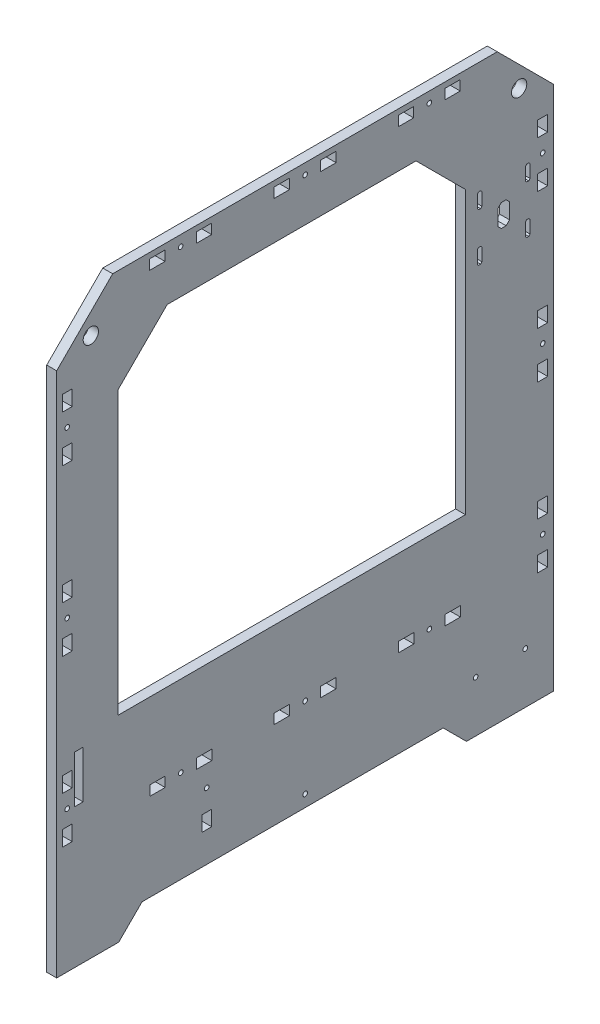
SolidWorks part; units mm, degrees
ref_plane "Front Plane" through (0, 0, 0) normal (0, 0, 1) x (1, 0, 0)
ref_plane "Top Plane" through (0, 0, 0) normal (0, 1, 0) x (1, 0, 0)
ref_plane "Right Plane" through (0, 0, 0) normal (1, 0, 0) x (0, 0, -1)
sketch "Sketch1" plane through (0, 0, 0) normal (1, 0, 0) x (0, 0, -1)
  line L0 (-34.3717, -25.3248) -> (-34.3717, -206.8248)
  line L1 (-37.635, 41.2752) -> (210.165, 41.2752)
  line L3 (-56.735, -213.3748) -> (-56.735, -243.8748)
  line L4 (228.265, -268.8248) -> (196.265, -300.8248) construction
  line L7 (230.4513, -30.9236) -> (229.2087, -30.9236)
  line L9 (176.665, 34.4752) -> (156.065, 34.4752) construction
  line L10 (230.4513, -40.9255) -> (229.2087, -40.9255)
  line L11 (215.8783, -58.6805) -> (212.7717, -58.6805)
  line L14 (200.33, -31.8023) -> (199.4513, -30.9236)
  line L15 (199.4513, -30.9236) -> (198.2087, -30.9236)
  line L16 (198.2087, -30.9236) -> (197.33, -31.8023)
  line L17 (197.33, -31.8023) -> (197.33, -40.0468)
  line L18 (199.4513, -40.9255) -> (198.2087, -40.9255)
  line L19 (228.33, -40.0468) -> (228.33, -31.8023)
  line L21 (200.33, -40.0468) -> (200.33, -31.8023)
  line L22 (231.33, -31.8023) -> (230.4513, -30.9236)
  line L25 (198.2087, -40.9255) -> (197.33, -40.0468)
  line L26 (200.33, -40.0468) -> (199.4513, -40.9255)
  line L28 (231.33, -31.8023) -> (231.33, -40.0468)
  line L30 (231.33, -40.0468) -> (230.4513, -40.9255)
  line L31 (229.2087, -30.9236) -> (228.33, -31.8023)
  line L32 (96.665, 34.4752) -> (76.065, 34.4752) construction
  line L34 (16.465, 34.4752) -> (-4.135, 34.4752) construction
  line L35 (-73.735, 5.1752) -> (-73.735, -333.6748)
  line L36 (-34.3717, -206.8248) -> (189.675, -206.8248)
  line L37 (-66.935, -19.5248) -> (-66.935, -40.1248) construction
  line L38 (-73.735, 5.1752) -> (-37.635, 41.2752)
  line L39 (-66.935, -125.9248) -> (-66.935, -146.5248) construction
  line L40 (189.675, -206.8248) -> (189.675, -25.3248)
  line L41 (-66.935, -232.3248) -> (-66.935, -252.9248) construction
  line L42 (246.265, 5.1752) -> (246.265, -333.6748)
  line L43 (-4.035, -259.1248) -> (16.565, -259.1248) construction
  line L44 (176.765, -259.1248) -> (156.165, -259.1248) construction
  line L45 (229.2087, -40.9255) -> (228.33, -40.0468)
  line L46 (230.4513, -61.9236) -> (229.2087, -61.9236)
  line L47 (230.4513, -71.9255) -> (229.2087, -71.9255)
  line L49 (96.665, -259.1248) -> (76.065, -259.1248) construction
  line L50 (239.465, -232.3248) -> (239.465, -252.9248) construction
  line L51 (228.33, -71.0468) -> (228.33, -62.8023)
  line L52 (231.33, -62.8023) -> (230.4513, -61.9236)
  line L55 (231.33, -62.8023) -> (231.33, -71.0468)
  line L56 (246.265, 5.1752) -> (210.165, 41.2752)
  line L57 (231.33, -71.0468) -> (230.4513, -71.9255)
  line L58 (229.2087, -61.9236) -> (228.33, -62.8023)
  line L60 (229.2087, -71.9255) -> (228.33, -71.0468)
  line L61 (199.4513, -61.9236) -> (198.2087, -61.9236)
  line L62 (199.4513, -71.9255) -> (198.2087, -71.9255)
  line L63 (175.325, -318.6748) -> (190.325, -333.6748)
  line L66 (200.33, -62.8023) -> (199.4513, -61.9236)
  line L67 (239.465, -125.9248) -> (239.465, -146.5248) construction
  line L68 (239.465, -19.5248) -> (239.465, -40.1248) construction
  line L69 (197.33, -62.8023) -> (197.33, -71.0468)
  line L71 (175.325, -318.6748) -> (-18.7217, -318.6748)
  line L72 (-18.7217, -318.6748) -> (-33.7217, -333.6748)
  line L73 (-73.735, -333.6748) -> (-33.7217, -333.6748)
  line L75 (190.325, -333.6748) -> (246.265, -333.6748)
  line L77 (200.33, -71.0468) -> (199.4513, -71.9255)
  line L78 (198.2087, -61.9236) -> (197.33, -62.8023)
  line L79 (200.33, -71.0468) -> (200.33, -62.8023)
  line L80 (198.2087, -71.9255) -> (197.33, -71.0468)
  line L83 (218.075, -46.3772) -> (215.8783, -44.1805)
  line L85 (215.8783, -44.1805) -> (212.7717, -44.1805)
  line L86 (212.7717, -44.1805) -> (210.575, -46.3772)
  line L89 (210.575, -56.4838) -> (210.575, -46.3772)
  line L90 (212.7717, -58.6805) -> (210.575, -56.4838)
  line L91 (218.075, -56.4838) -> (215.8783, -58.6805)
  line L92 (218.075, -46.3772) -> (218.075, -56.4838)
  line L97 (157.825, 6.5252) -> (189.675, -25.3248)
  line L98 (-2.5217, 6.5252) -> (-34.3717, -25.3248)
  line L101 (216.7582, -291.8247) -> (216.7582, -279.422) construction
  line L104 (-62.085, -243.8748) -> (-56.735, -243.8748)
  line L107 (236.265, -40.1248) -> (242.665, -40.1248)
  line L108 (242.665, -40.1248) -> (242.665, -49.5248)
  line L110 (242.665, -49.5248) -> (236.265, -49.5248)
  line L111 (236.265, -40.1248) -> (236.265, -49.5248)
  line L112 (-62.085, -243.8748) -> (-62.085, -213.3748)
  line L117 (-62.085, -213.3748) -> (-56.735, -213.3748)
  line L123 (204.6582, -279.985) -> (204.6582, -291.8245) construction
  line L135 (210.7082, -291.8247) -> (210.7082, -279.422) construction
  line L138 (210.7082, -279.422) -> (210.7082, -291.8247) construction
  line L139 (204.6582, -291.8245) -> (204.6582, -279.985) construction
  line L140 (219.8677, -279.985) -> (219.8677, -291.8245) construction
  line L141 (219.8677, -291.8245) -> (219.8677, -279.985) construction
  line L142 (213.8177, -279.422) -> (213.8177, -291.8245) construction
  line L143 (207.7677, -279.422) -> (210.7082, -279.422) construction
  line L144 (207.7677, -279.422) -> (207.7677, -291.8243) construction
  line L146 (208.3001, -296.5891) -> (208.3001, -300.389) construction
  line L147 (204.8001, -300.389) -> (204.8001, -296.5891) construction
  line L148 (219.7299, -300.389) -> (219.7299, -296.5891) construction
  line L149 (216.2299, -296.5891) -> (216.2299, -300.389) construction
  line L150 (208.3304, -276.3128) -> (216.1954, -276.3128) construction
  line L151 (216.1954, -276.3128) -> (208.3304, -276.3128) construction
  line L152 (216.7582, -279.422) -> (216.7582, -291.8247) construction
  line L154 (216.7582, -279.422) -> (213.8177, -279.422) construction
  line L155 (207.7677, -291.8243) -> (207.7677, -279.422) construction
  line L159 (210.7082, -279.422) -> (207.7677, -279.422) construction
  line L160 (213.8177, -291.8245) -> (213.8177, -279.422) construction
  line L161 (213.8177, -279.422) -> (216.7582, -279.422) construction
  line L162 (210.515, -296.5891) -> (210.515, -302.0139) construction
  line L163 (214.015, -296.5891) -> (214.015, -302.0139) construction
  line L164 (230.6429, -276.8104) -> (230.6429, -292.7391) construction
  line L165 (221.5989, -298.2391) -> (221.5989, -271.3104) construction
  line L166 (212.265, -272.9604) -> (212.265, -296.5891) construction
  line L167 (202.6784, -284.7747) -> (221.8516, -284.7747) construction
  line L168 (212.2671, -293.3368) -> (212.2629, -276.3128) construction
  line L170 (193.8871, -276.8104) -> (193.8871, -292.7391) construction
  line L171 (197.3871, -292.7391) -> (197.3871, -276.8104) construction
  line L172 (214.015, -272.9604) -> (214.015, -267.5355) construction
  line L173 (225.0989, -271.3104) -> (225.0989, -298.2391) construction
  line L174 (227.1429, -292.7391) -> (227.1429, -276.8104) construction
  line L175 (210.515, -272.9604) -> (210.515, -267.5355) construction
  line L176 (216.2299, -272.9604) -> (216.2299, -269.1604) construction
  line L177 (199.4311, -271.3104) -> (199.4311, -298.2391) construction
  line L178 (219.7299, -269.1604) -> (219.7299, -272.9604) construction
  line L179 (204.8001, -269.1604) -> (204.8001, -272.9604) construction
  line L180 (208.3001, -272.9604) -> (208.3001, -269.1604) construction
  line L181 (202.9311, -298.2391) -> (202.9311, -271.3104) construction
  line L193 (-2.5217, 6.5252) -> (157.825, 6.5252)
  line L194 (199.4513, -33.9236) -> (199.8907, -33.4842) [skipped]
  line L195 (198.2087, -33.9236) -> (198.83, -33.9236) [skipped]
  line L196 (197.33, -33.0449) -> (197.7693, -33.4842) [skipped]
  line L197 (212.7717, -51.6805) -> (215.8783, -51.6805) [skipped]
  line L198 (215.8783, -51.6805) -> (218.075, -49.4838) [skipped]
  line L199 (210.575, -49.4838) -> (212.7717, -51.6805) [skipped]
  line L200 (218.075, -49.4838) -> (218.075, -46.3772) [skipped]
  line L201 (210.575, -46.3772) -> (210.575, -49.4838) [skipped]
  circle A0 centre (6.165, 34.4752) radius 1.5
  circle A1 centre (86.365, 34.4752) radius 1.5
  circle A2 centre (166.365, 34.4752) radius 1.5
  circle A3 centre (86.365, -259.1248) radius 1.5
  circle A4 centre (166.465, -259.1248) radius 1.5
  circle A5 centre (6.265, -259.1248) radius 1.5
  circle A6 centre (239.465, -29.8248) radius 1.5
  circle A7 centre (239.465, -136.2248) radius 1.5
  circle A8 centre (239.465, -242.6248) radius 1.5
  circle A9 centre (-66.935, -242.6248) radius 1.5
  circle A10 centre (-66.935, -136.2248) radius 1.5
  circle A11 centre (-66.935, -29.8248) radius 1.5
  circle A12 centre (198.83, -32.4236) radius 1.5 construction
  circle A13 centre (224.265, 13.8002) radius 4.925
  circle A14 centre (-51.735, 13.8002) radius 4.925
  circle A15 centre (229.83, -39.4255) radius 1.5 construction
  circle A16 centre (229.83, -32.4236) radius 1.5 construction
  circle A17 centre (229.83, -70.4255) radius 1.5 construction
  circle A18 centre (229.83, -63.4236) radius 1.5 construction
  circle A19 centre (198.83, -39.4255) radius 1.5 construction
  circle A20 centre (198.83, -70.4255) radius 1.5 construction
  circle A21 centre (198.83, -63.4236) radius 1.5 construction
  circle A22 centre (196.265, -268.8248) radius 1.5 construction
  circle A23 centre (228.265, -268.8248) radius 1.5 construction
  circle A24 centre (214.325, -47.9305) radius 3.75 construction
  circle A26 centre (228.265, -300.8248) radius 1.5
  circle A27 centre (196.265, -300.8248) radius 1.5
  circle A28 centre (214.325, -54.9305) radius 3.75 construction
  arc A42 (221.5989, -271.3104) -> (225.0989, -271.3104) centre (223.3489, -271.3104) cw construction
  arc A45 (227.1429, -276.8104) -> (230.6429, -276.8104) centre (228.8929, -276.8104) cw construction
  arc A46 (210.7082, -291.8247) -> (212.2671, -293.3368) centre (212.2209, -291.8247) ccw construction
  arc A51 (219.8677, -279.985) -> (216.1954, -276.3128) centre (216.1954, -279.985) ccw construction
  arc A64 (208.3304, -276.3128) -> (204.6582, -279.985) centre (208.3304, -279.985) ccw construction
  arc A67 (212.2671, -293.3368) -> (213.8177, -291.8245) centre (212.3049, -291.8245) ccw construction
  arc A68 (227.1429, -292.7391) -> (230.6429, -292.7391) centre (228.8929, -292.7391) ccw construction
  arc A69 (221.5989, -298.2391) -> (225.0989, -298.2391) centre (223.3489, -298.2391) ccw construction
  arc A70 (208.3001, -296.5891) -> (204.8001, -296.5891) centre (206.5501, -296.5891) ccw construction
  arc A71 (204.8001, -300.389) -> (208.3001, -300.389) centre (206.5501, -300.389) ccw construction
  arc A72 (219.7299, -300.389) -> (216.2299, -300.389) centre (217.9799, -300.389) cw construction
  arc A73 (202.9311, -271.3104) -> (199.4311, -271.3104) centre (201.1811, -271.3104) ccw construction
  arc A74 (197.3871, -276.8104) -> (193.8871, -276.8104) centre (195.6371, -276.8104) ccw construction
  arc A75 (197.3871, -292.7391) -> (193.8871, -292.7391) centre (195.6371, -292.7391) cw construction
  arc A76 (210.515, -272.9604) -> (214.015, -272.9604) centre (212.265, -272.9604) ccw construction
  arc A77 (214.015, -267.5355) -> (210.515, -267.5355) centre (212.265, -267.5355) ccw construction
  arc A78 (216.2299, -272.9604) -> (219.7299, -272.9604) centre (217.9799, -272.9604) ccw construction
  arc A79 (219.7299, -269.1604) -> (216.2299, -269.1604) centre (217.9799, -269.1604) ccw construction
  arc A80 (204.8001, -269.1604) -> (208.3001, -269.1604) centre (206.5501, -269.1604) cw construction
  arc A81 (202.9311, -298.2391) -> (199.4311, -298.2391) centre (201.1811, -298.2391) cw construction
  arc A82 (208.3001, -272.9604) -> (204.8001, -272.9604) centre (206.5501, -272.9604) cw construction
  arc A83 (216.2299, -296.5891) -> (219.7299, -296.5891) centre (217.9799, -296.5891) cw construction
  arc A84 (204.6582, -291.8245) -> (206.2171, -293.3366) centre (206.1709, -291.8245) ccw construction
  arc A85 (219.8677, -279.985) -> (216.1954, -276.3128) centre (216.1954, -279.985) ccw construction
  arc A86 (214.015, -302.0139) -> (210.515, -302.0139) centre (212.265, -302.0139) cw construction
  arc A87 (210.515, -296.5891) -> (214.015, -296.5891) centre (212.265, -296.5891) cw construction
  arc A88 (216.7582, -291.8245) -> (218.3129, -293.3367) centre (218.2709, -291.8245) ccw construction
  arc A89 (206.2171, -293.3366) -> (207.7677, -291.8243) centre (206.2549, -291.8243) ccw construction
  arc A90 (208.3304, -276.3128) -> (204.6582, -279.985) centre (208.3304, -279.985) ccw construction
  arc A91 (218.3129, -293.3367) -> (219.8677, -291.8245) centre (218.3549, -291.8245) ccw construction
  ellipse E6 centre (218.3549, -291.8245) end of major axis (219.4247, -292.8943) minor radius 1.5126 (218.3554, -293.3373) -> (219.8677, -291.8245) ccw construction
  ellipse E7 centre (212.2209, -291.8247) end of major axis (211.1513, -292.8944) minor radius 1.5127 (210.7082, -291.8247) -> (212.2205, -293.3375) ccw construction
  ellipse E8 centre (212.3049, -291.8245) end of major axis (211.2352, -290.7548) minor radius 1.5126 (212.3054, -293.3372) -> (213.8177, -291.8245) ccw construction
  ellipse E9 centre (206.1709, -291.8245) end of major axis (207.2407, -290.7548) minor radius 1.5126 (204.6582, -291.8245) -> (206.1705, -293.3373) ccw construction
  ellipse E10 centre (218.2709, -291.8245) end of major axis (217.2012, -292.8943) minor radius 1.5126 (216.7582, -291.8247) -> (218.2705, -293.3373) ccw construction
  ellipse E11 centre (206.2549, -291.8243) end of major axis (207.3247, -292.894) minor radius 1.5126 (206.2554, -293.337) -> (207.7677, -291.8243) ccw construction
extrude "Boss-Extrude1" add sketch "Sketch1" along normal blind 6.4
sketch "Sketch2" plane through (6.4, 0, 0) normal (1, 0, 0) x (0, 0, -1)
  line L0 (239.465, -257.6248) -> (239.465, -227.6248) construction
  line L1 (242.665, -262.5748) -> (242.665, -252.6748)
  line L2 (236.265, -222.6748) -> (242.665, -222.6748)
  line L3 (236.265, -252.6748) -> (242.665, -252.6748)
  line L4 (236.265, -262.5748) -> (242.665, -262.5748)
  line L5 (236.265, -257.6248) -> (242.665, -257.6248) construction
  line L6 (236.265, -232.5748) -> (242.665, -232.5748)
  line L7 (236.265, -262.5748) -> (236.265, -252.6748)
  line L8 (236.265, -227.6248) -> (242.665, -227.6248) construction
  line L9 (236.265, -222.6748) -> (236.265, -232.5748)
  line L10 (242.665, -222.6748) -> (242.665, -232.5748)
  line L11 (-70.135, -252.6748) -> (-63.735, -252.6748)
  line L12 (-70.135, -262.5748) -> (-70.135, -252.6748)
  line L13 (-66.935, -257.6248) -> (-66.935, -227.6248) construction
  line L14 (-70.135, -222.6748) -> (-63.735, -222.6748)
  line L15 (-63.735, -262.5748) -> (-63.735, -252.6748)
  line L16 (-70.135, -232.5748) -> (-63.735, -232.5748)
  line L17 (-63.735, -222.6748) -> (-63.735, -232.5748)
  line L18 (-70.135, -227.6248) -> (-63.735, -227.6248) construction
  line L19 (-70.135, -262.5748) -> (-63.735, -262.5748)
  line L20 (-70.135, -222.6748) -> (-70.135, -232.5748)
  line L21 (-70.135, -257.6248) -> (-63.735, -257.6248) construction
  line L22 (-70.135, -146.2748) -> (-63.735, -146.2748)
  line L23 (-70.135, -156.1748) -> (-70.135, -146.2748)
  line L24 (-66.935, -151.2248) -> (-66.935, -121.2248) construction
  line L25 (-70.135, -116.2748) -> (-63.735, -116.2748)
  line L26 (-63.735, -156.1748) -> (-63.735, -146.2748)
  line L27 (-70.135, -126.1748) -> (-63.735, -126.1748)
  line L28 (-63.735, -116.2748) -> (-63.735, -126.1748)
  line L29 (-70.135, -121.2248) -> (-63.735, -121.2248) construction
  line L30 (-70.135, -156.1748) -> (-63.735, -156.1748)
  line L31 (-70.135, -116.2748) -> (-70.135, -126.1748)
  line L32 (-70.135, -151.2248) -> (-63.735, -151.2248) construction
  line L33 (-70.135, -39.8748) -> (-63.735, -39.8748)
  line L34 (-70.135, -49.7748) -> (-70.135, -39.8748)
  line L35 (-66.935, -44.8248) -> (-66.935, -14.8248) construction
  line L36 (-70.135, -9.8748) -> (-63.735, -9.8748)
  line L37 (-63.735, -49.7748) -> (-63.735, -39.8748)
  line L38 (-70.135, -19.7748) -> (-63.735, -19.7748)
  line L39 (-63.735, -9.8748) -> (-63.735, -19.7748)
  line L40 (-70.135, -14.8248) -> (-63.735, -14.8248) construction
  line L41 (-70.135, -49.7748) -> (-63.735, -49.7748)
  line L42 (-70.135, -9.8748) -> (-70.135, -19.7748)
  line L43 (-70.135, -44.8248) -> (-63.735, -44.8248) construction
  line L44 (236.265, -116.2748) -> (236.265, -126.1748)
  line L45 (242.665, -156.1748) -> (242.665, -146.2748)
  line L46 (236.265, -126.1748) -> (242.665, -126.1748)
  line L47 (236.265, -116.2748) -> (242.665, -116.2748)
  line L48 (236.265, -156.1748) -> (236.265, -146.2748)
  line L49 (242.665, -116.2748) -> (242.665, -126.1748)
  line L50 (236.265, -156.1748) -> (242.665, -156.1748)
  line L51 (236.265, -121.2248) -> (242.665, -121.2248) construction
  line L52 (239.465, -151.2248) -> (239.465, -121.2248) construction
  line L53 (236.265, -146.2748) -> (242.665, -146.2748)
  line L54 (236.265, -151.2248) -> (242.665, -151.2248) construction
  line L55 (236.265, -9.8748) -> (236.265, -19.7748)
  line L56 (242.665, -49.7748) -> (242.665, -39.8748)
  line L57 (236.265, -19.7748) -> (242.665, -19.7748)
  line L58 (236.265, -9.8748) -> (242.665, -9.8748)
  line L59 (236.265, -49.7748) -> (236.265, -39.8748)
  line L60 (242.665, -9.8748) -> (242.665, -19.7748)
  line L61 (236.265, -49.7748) -> (242.665, -49.7748)
  line L62 (236.265, -14.8248) -> (242.665, -14.8248) construction
  line L63 (239.465, -44.8248) -> (239.465, -14.8248) construction
  line L64 (236.265, -39.8748) -> (242.665, -39.8748)
  line L65 (236.265, -44.8248) -> (242.665, -44.8248) construction
  line L66 (71.365, -259.1248) -> (101.365, -259.1248) construction
  line L67 (66.415, -262.3248) -> (76.315, -262.3248)
  line L68 (106.315, -255.9248) -> (106.315, -262.3248)
  line L69 (76.315, -255.9248) -> (76.315, -262.3248)
  line L70 (66.415, -255.9248) -> (66.415, -262.3248)
  line L71 (71.365, -255.9248) -> (71.365, -262.3248) construction
  line L72 (96.415, -255.9248) -> (96.415, -262.3248)
  line L73 (66.415, -255.9248) -> (76.315, -255.9248)
  line L74 (101.365, -255.9248) -> (101.365, -262.3248) construction
  line L75 (106.315, -255.9248) -> (96.415, -255.9248)
  line L76 (106.315, -262.3248) -> (96.415, -262.3248)
  line L77 (151.465, -259.1248) -> (181.465, -259.1248) construction
  line L78 (146.515, -262.3248) -> (156.415, -262.3248)
  line L79 (186.415, -255.9248) -> (186.415, -262.3248)
  line L80 (156.415, -255.9248) -> (156.415, -262.3248)
  line L81 (146.515, -255.9248) -> (146.515, -262.3248)
  line L82 (151.465, -255.9248) -> (151.465, -262.3248) construction
  line L83 (176.515, -255.9248) -> (176.515, -262.3248)
  line L84 (146.515, -255.9248) -> (156.415, -255.9248)
  line L85 (181.465, -255.9248) -> (181.465, -262.3248) construction
  line L86 (186.415, -255.9248) -> (176.515, -255.9248)
  line L87 (186.415, -262.3248) -> (176.515, -262.3248)
  line L88 (151.365, 34.4752) -> (181.365, 34.4752) construction
  line L89 (146.415, 31.2752) -> (156.315, 31.2752)
  line L90 (186.315, 37.6752) -> (186.315, 31.2752)
  line L91 (156.315, 37.6752) -> (156.315, 31.2752)
  line L92 (146.415, 37.6752) -> (146.415, 31.2752)
  line L93 (151.365, 37.6752) -> (151.365, 31.2752) construction
  line L94 (176.415, 37.6752) -> (176.415, 31.2752)
  line L95 (146.415, 37.6752) -> (156.315, 37.6752)
  line L96 (181.365, 37.6752) -> (181.365, 31.2752) construction
  line L97 (186.315, 37.6752) -> (176.415, 37.6752)
  line L98 (186.315, 31.2752) -> (176.415, 31.2752)
  line L99 (-8.735, -259.1248) -> (21.265, -259.1248) construction
  line L100 (21.265, -255.9248) -> (21.265, -262.3248) construction
  line L101 (-8.735, -255.9248) -> (-8.735, -262.3248) construction
  line L102 (-13.685, -255.9248) -> (-13.685, -262.3248)
  line L103 (-13.685, -262.3248) -> (-3.785, -262.3248)
  line L104 (26.215, -255.9248) -> (16.315, -255.9248)
  line L105 (16.315, -255.9248) -> (16.315, -262.3248)
  line L106 (26.215, -255.9248) -> (26.215, -262.3248)
  line L107 (26.215, -262.3248) -> (16.315, -262.3248)
  line L108 (-13.685, -255.9248) -> (-3.785, -255.9248)
  line L109 (-3.785, -255.9248) -> (-3.785, -262.3248)
  line L110 (71.365, 34.4752) -> (101.365, 34.4752) construction
  line L111 (66.415, 31.2752) -> (76.315, 31.2752)
  line L112 (106.315, 37.6752) -> (106.315, 31.2752)
  line L113 (76.315, 37.6752) -> (76.315, 31.2752)
  line L114 (66.415, 37.6752) -> (66.415, 31.2752)
  line L115 (71.365, 37.6752) -> (71.365, 31.2752) construction
  line L116 (96.415, 37.6752) -> (96.415, 31.2752)
  line L117 (66.415, 37.6752) -> (76.315, 37.6752)
  line L118 (101.365, 37.6752) -> (101.365, 31.2752) construction
  line L119 (106.315, 37.6752) -> (96.415, 37.6752)
  line L120 (106.315, 31.2752) -> (96.415, 31.2752)
  line L121 (-8.835, 34.4752) -> (21.165, 34.4752) construction
  line L122 (-13.785, 31.2752) -> (-3.885, 31.2752)
  line L123 (26.115, 37.6752) -> (26.115, 31.2752)
  line L124 (-3.885, 37.6752) -> (-3.885, 31.2752)
  line L125 (-13.785, 37.6752) -> (-13.785, 31.2752)
  line L126 (-8.835, 37.6752) -> (-8.835, 31.2752) construction
  line L127 (16.215, 37.6752) -> (16.215, 31.2752)
  line L128 (-13.785, 37.6752) -> (-3.885, 37.6752)
  line L129 (21.165, 37.6752) -> (21.165, 31.2752) construction
  line L130 (26.115, 37.6752) -> (16.215, 37.6752)
  line L131 (26.115, 31.2752) -> (16.215, 31.2752)
  line L134 (19.765, -289.4248) -> (26.165, -289.4248)
  line L135 (19.765, -289.4248) -> (19.765, -299.2248)
  line L136 (19.765, -299.2248) -> (26.165, -299.2248)
  line L137 (26.165, -289.4248) -> (26.165, -299.2248)
  circle A0 centre (22.965, -275.8748) radius 1.5
  circle A1 centre (86.365, -311.0248) radius 1.5
  dimension "D6" = 3
  dimension "D8" = 3
  dimension "D2" = 30
  dimension "D4" = 6.4
  dimension "D5" = 9.8
  dimension "D14" = 9.9
  dimension "D15" = 6.4
extrude "Cut-Extrude1" cut sketch "Sketch2" against normal through all
